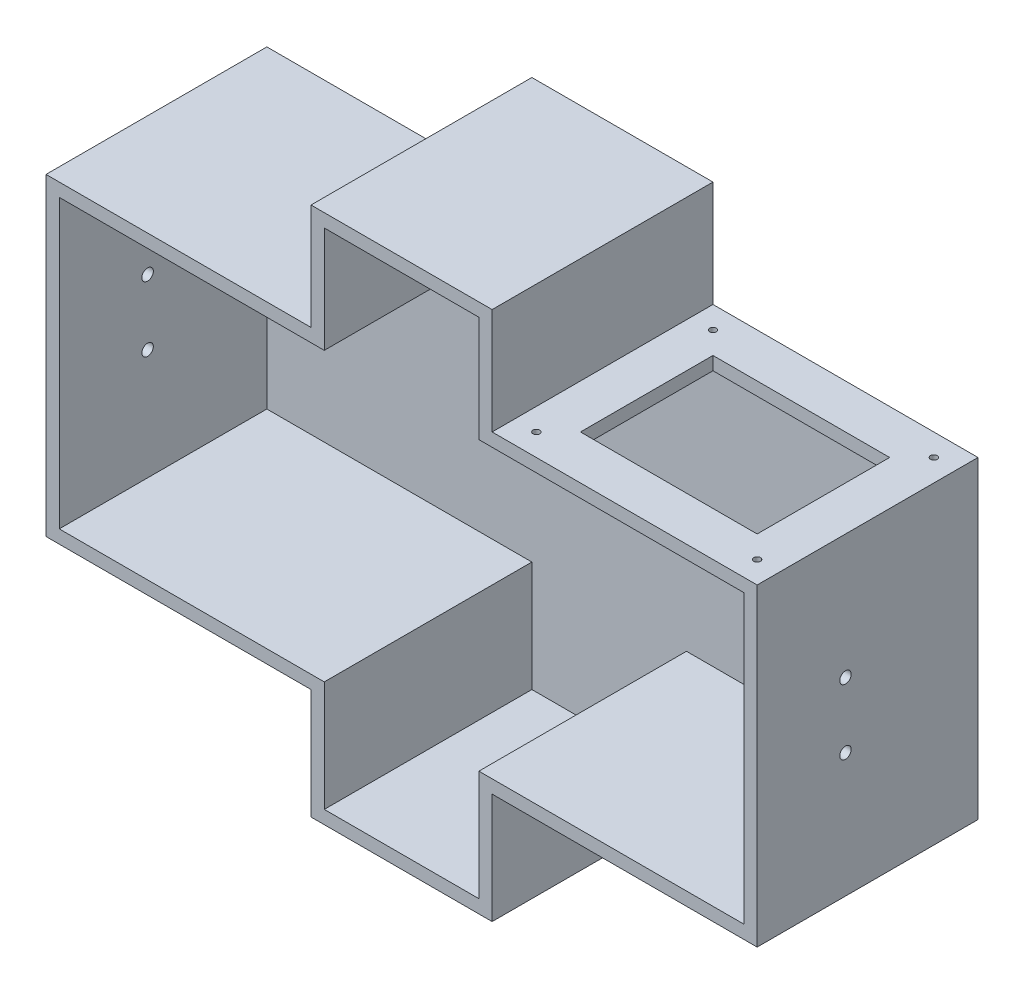
SolidWorks part; units mm, degrees
ref_plane "Alzado" through (0, 0, 0) normal (0, 0, 1) x (1, 0, 0)
ref_plane "Planta" through (0, 0, 0) normal (0, 1, 0) x (1, 0, 0)
ref_plane "Vista lateral" through (0, 0, 0) normal (1, 0, 0) x (0, 0, -1)
sketch "Croquis1" plane through (0, 0, 0) normal (0, 0, 1) x (1, 0, 0)
  line L0 (155, 66) -> (35, 66)
  line L1 (35, 66) -> (35, 114)
  line L2 (35, 114) -> (-35, 114)
  line L3 (-35, 114) -> (-35, 66)
  line L4 (-35, 66) -> (-155, 66)
  line L5 (-155, 66) -> (-155, -64)
  line L6 (-155, -64) -> (-35, -64)
  line L7 (-35, -64) -> (-35, -114)
  line L8 (-35, -114) -> (35, -114)
  line L9 (35, -114) -> (35, -64)
  line L10 (35, -64) -> (155, -64)
  line L11 (155, -64) -> (155, 66)
  line L12 (-41, 72) -> (-161, 72)
  line L13 (-161, 72) -> (-161, -70)
  line L14 (-161, -70) -> (-41, -70)
  line L15 (-41, -70) -> (-41, -120)
  line L16 (-41, -120) -> (41, -120)
  line L17 (41, -120) -> (41, -70)
  line L18 (41, -70) -> (161, -70)
  line L19 (161, -70) -> (161, 72)
  line L20 (161, 72) -> (41, 72)
  line L21 (41, 72) -> (41, 120)
  line L22 (41, 120) -> (-41, 120)
  line L23 (-41, 120) -> (-41, 72)
  dimension "D1" = 310
  dimension "D2" = 130
  dimension "D3" = 120
  dimension "D4" = 120
  dimension "D5" = 48
  dimension "D6" = 70
  dimension "D7" = 50
  dimension "D8" = 70
  dimension "D9" = 120
  dimension "D10" = 90
  dimension "D11" = 155
  dimension "D12" = 66
  dimension "D13" = 35
  dimension "D14" = 6
extrude "Saliente-Extruir1" add sketch "Croquis1" along normal blind 100
sketch "Croquis2" plane through (0, 0, 0) normal (0, 0, -1) x (-1, 0, 0)
  line L12 (41, 72) -> (41, 120)
  line L13 (41, 120) -> (-41, 120)
  line L14 (-41, 120) -> (-41, 72)
  line L15 (-41, 72) -> (-161, 72)
  line L16 (-161, 72) -> (-161, -70)
  line L17 (-161, -70) -> (-41, -70)
  line L18 (-41, -70) -> (-41, -120)
  line L19 (-41, -120) -> (41, -120)
  line L20 (41, -120) -> (41, -70)
  line L21 (41, -70) -> (161, -70)
  line L22 (161, -70) -> (161, 72)
  line L23 (161, 72) -> (41, 72)
  line L24 (41, 72) -> (41, 120)
  line L25 (41, 120) -> (-41, 120)
  line L26 (-41, 120) -> (-41, 72)
  line L27 (-41, 72) -> (-161, 72)
  line L28 (-161, 72) -> (-161, -70)
  line L29 (-161, -70) -> (-41, -70)
  line L30 (-41, -70) -> (-41, -120)
  line L31 (-41, -120) -> (41, -120)
  line L32 (41, -120) -> (41, -70)
  line L33 (41, -70) -> (161, -70)
  line L34 (161, -70) -> (161, 72)
  line L35 (161, 72) -> (41, 72)
  dimension "D1" = 0
extrude "Saliente-Extruir2" add sketch "Croquis2" against normal blind 6
sketch "Croquis4" plane through (0, 72, 0) normal (0, 1, 0) x (1, 0, 0)
  line L4 (141, -80) -> (141, -20)
  line L5 (141, -20) -> (61, -20)
  line L6 (61, -20) -> (61, -80)
  line L7 (61, -80) -> (141, -80)
  line L8 (151, -90) -> (151, -10)
  line L9 (151, -10) -> (51, -10)
  line L10 (51, -10) -> (51, -90)
  line L11 (51, -90) -> (151, -90)
  line L12 (151, -90) -> (151, -10) construction
  line L13 (151, -10) -> (51, -10) construction
  line L14 (51, -10) -> (51, -90) construction
  line L15 (51, -90) -> (151, -90) construction
  circle A0 centre (151, -90) radius 1.5
  circle A1 centre (51, -90) radius 1.5
  circle A2 centre (51, -10) radius 1.5
  circle A3 centre (151, -10) radius 1.5
  dimension "D3" = 3
  dimension "D4" = 3
  dimension "D5" = 3
  dimension "D6" = 3
  dimension "D1" = 10
  dimension "D2" = 10
extrude "Cortar-Extruir2" cut sketch "Croquis4" against normal blind 6
sketch "Croquis5" plane through (161, 0, 0) normal (1, 0, 0) x (0, 0, -1)
  line L0 (-100, 1) -> (47.047, 1) construction
  line L1 (-100, -70) -> (-100, 72) construction
  circle A0 centre (-60, -13.75) radius 2.6
  circle A1 centre (-60, 15.75) radius 2.6
  dimension "D1" = 5.2
  dimension "D2" = 5.2
  dimension "D3" = 14.75
  dimension "D4" = 14.75
  dimension "D5" = 40
  dimension "D6" = 40
extrude "Cortar-Extruir3" cut sketch "Croquis5" against normal through all
